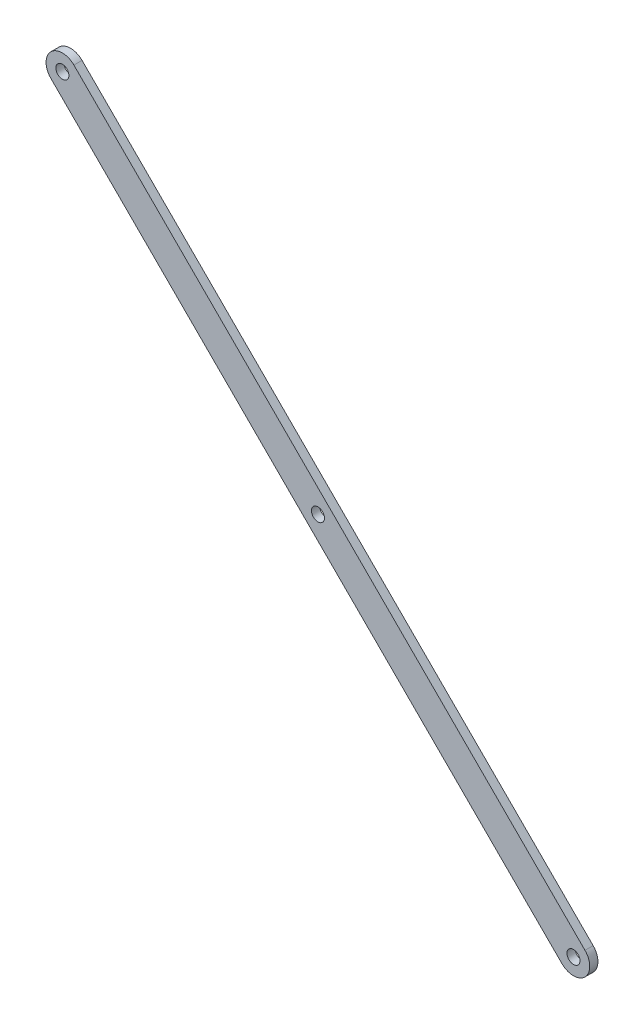
SolidWorks part; units mm, degrees
ref_plane "Alzado" through (0, 0, 0) normal (0, 0, 1) x (1, 0, 0)
ref_plane "Planta" through (0, 0, 0) normal (0, 1, 0) x (1, 0, 0)
ref_plane "Vista lateral" through (0, 0, 0) normal (1, 0, 0) x (0, 0, -1)
sketch "Croquis2" plane through (0, 0, 0) normal (0, 0, 1) x (1, 0, 0)
  line L0 (0, 0) -> (-81.1145, 0) construction
  line L1 (0, 0) -> (-64.5633, 64.5633) construction
  line L2 (0, 0) -> (-313.6726, 313.6726) construction
  line L3 (-7.0711, -7.0711) -> (-320.7436, 306.6015)
  line L4 (7.0711, 7.0711) -> (-306.6015, 320.7436)
  arc A0 (-7.0711, -7.0711) -> (7.0711, 7.0711) centre (0, 0) ccw
  arc A1 (-306.6015, 320.7436) -> (-320.7436, 306.6015) centre (-313.6726, 313.6726) ccw
  circle A2 centre (-313.6726, 313.6726) radius 4
  circle A3 centre (0, 0) radius 4
  circle A6 centre (-156.8363, 156.8363) radius 4
  point P4 (-156.8363, 156.8363)
  dimension "D3" = 8
  dimension "D1" = 45
  dimension "D2" = 443.6
  dimension "D4" = 20
extrude "Saliente-Extruir1" add sketch "Croquis2" along normal blind 5
